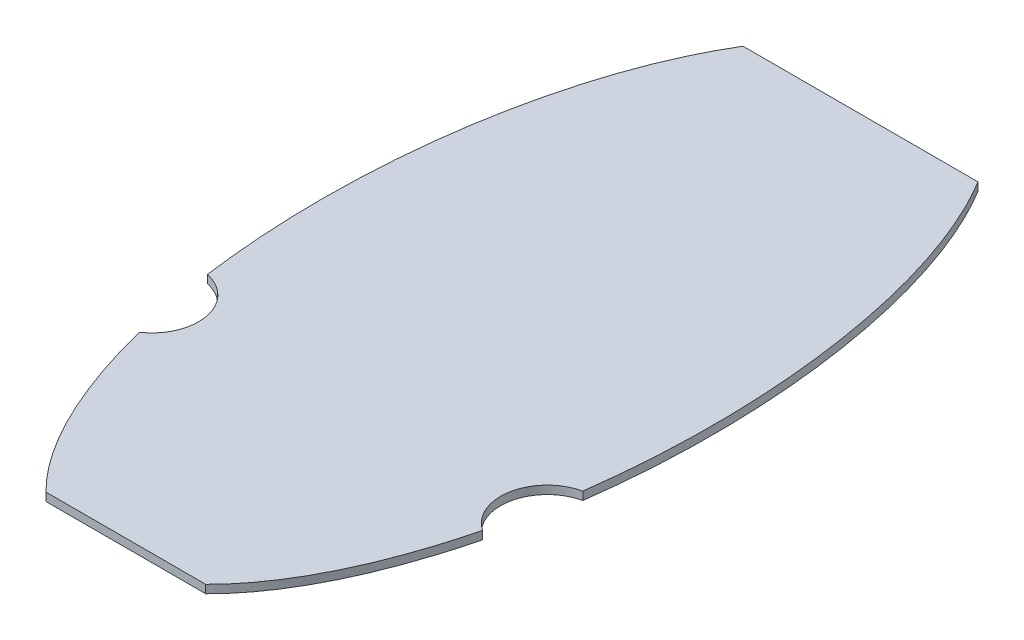
SolidWorks part; units mm, degrees
ref_plane "Front Plane" through (0, 0, 0) normal (0, 0, 1) x (1, 0, 0)
ref_plane "Top Plane" through (0, 0, 0) normal (0, 1, 0) x (1, 0, 0)
ref_plane "Right Plane" through (0, 0, 0) normal (1, 0, 0) x (0, 0, -1)
sketch "Sketch1" plane through (0, 0, 0) normal (0, 1, 0) x (1, 0, 0)
  line L0 (-5.4388, -26.67) -> (5.4388, -26.67)
  line L1 (-8.001, 23.368) -> (8.001, 23.368)
  ellipse E0 centre (0, 0) end of major axis (0, -29.21) minor radius 13.335 (5.4388, -26.67) -> (8.001, 23.368) ccw
  ellipse E1 centre (0, 0) end of major axis (0, -29.21) minor radius 13.335 (-8.001, 23.368) -> (-5.4388, -26.67) ccw
  dimension "D1" = 26.67
  dimension "D2" = 58.42
  dimension "D3" = 55.88
  dimension "D4" = 50.038
extrude "Boss-Extrude1" add sketch "Sketch1" along normal blind 0.5588
sketch "Sketch2" plane through (0, 0, 0) normal (0, 1, 0) x (1, 0, 0)
  line L0 (0, 0) -> (0, 56.6506) construction
  circle A0 centre (-13.462, -11.43) radius 3.175
  circle A1 centre (13.462, -11.43) radius 3.175
  dimension "D1" = 6.35
  dimension "D2" = 26.924
  dimension "D3" = 11.43
extrude "Cut-Extrude3" cut sketch "Sketch2" along normal through all
